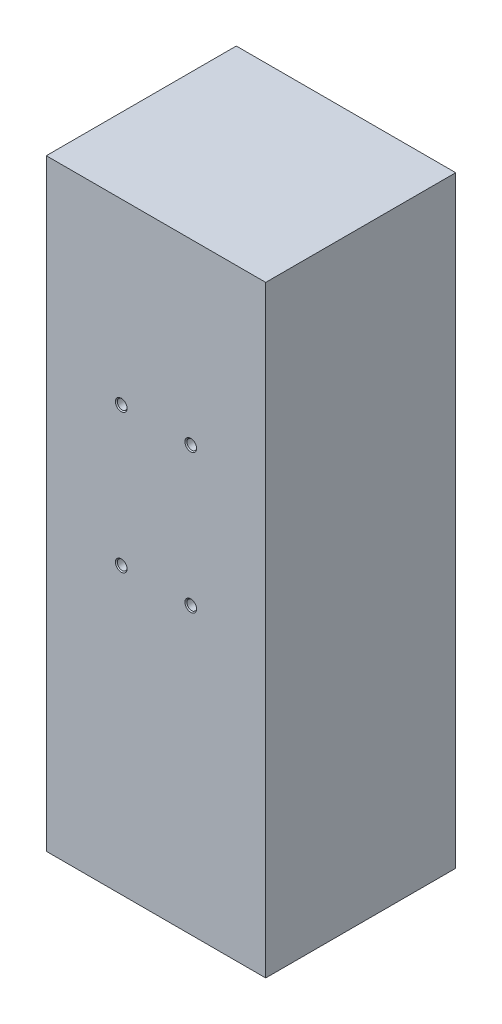
SolidWorks part; units mm, degrees
ref_plane "Front Plane" through (0, 0, 0) normal (0, 0, 1) x (1, 0, 0)
ref_plane "Top Plane" through (0, 0, 0) normal (0, 1, 0) x (1, 0, 0)
ref_plane "Right Plane" through (0, 0, 0) normal (1, 0, 0) x (0, 0, -1)
sketch "Sketch1" plane through (0, 0, 0) normal (0, 1, 0) x (1, 0, 0)
  line L1 (-47.35, -41) -> (47.35, -41)
  line L2 (-47.35, -41) -> (-47.35, 41)
  line L3 (-47.35, 41) -> (47.35, 41)
  line L4 (47.35, -41) -> (47.35, 41)
  line L5 (-47.35, -41) -> (47.35, 41) construction
  line L6 (-47.35, 41) -> (47.35, -41) construction
  point P0 (0, 0)
  dimension "D1" = 94.7
  dimension "D2" = 82
extrude "Boss-Extrude1" add sketch "Sketch1" along normal mid plane 260
sketch "Sketch2" plane through (0, 0, 41) normal (0, 0, 1) x (1, 0, 0)
  line L0 (-47.35, -130) -> (47.35, -130) construction
  line L1 (-15, -7) -> (15, -7) construction
  line L2 (-15, -7) -> (-15, 53) construction
  line L3 (-15, 53) -> (15, 53) construction
  line L4 (15, -7) -> (15, 53) construction
  line L5 (-15, -7) -> (15, 53) construction
  line L6 (-15, 53) -> (15, -7) construction
  line L7 (0, -7) -> (0, -130) construction
  circle A0 centre (15, 53) radius 3 construction
  circle A1 centre (-15, 53) radius 3 construction
  circle A2 centre (-15, -7) radius 3 construction
  circle A3 centre (15, -7) radius 3 construction
  point P0 (0, 23)
  dimension "D4" = 6
  dimension "D1" = 30
  dimension "D2" = 60
  dimension "D3" = 123
hole_wizard "M5x0.8 Tapped Hole1" positions "Sketch3" profile "Sketch4" tap size "M5x0.8" standard "ANSI Metric"
sketch "Sketch3" plane through (0, 0, 41) normal (0, 0, 1) x (1, 0, 0)
  point P0 (15, 53)
  point P3 (-15, 53)
  point P6 (-15, -7)
  point P9 (15, -7)
sketch "Sketch4" plane through (15, 53, 41) normal (1, 0, 0) x (0, -1, 0)
  line L0 (0, 0) -> (0, 13.6618)
  line L1 (0, 13.6618) -> (2.1, 12.4)
  line L2 (2.1, 12.4) -> (2.1, 0.425)
  line L3 (2.1, 0.425) -> (2.525, 0)
  line L5 (2.525, 0) -> (0, 0)
  line L6 (-2.1, 0.425) -> (-2.525, 0) construction
  line L10 (0, 13.6618) -> (-2.1, 12.4) construction
  line L11 (0, -6.35) -> (0, 107.95) construction
  dimension "Tap Drill Dia." = 4.2
  dimension "Tap Drill Depth" = 12.4
  dimension "Near C'Sink Dia." = 5.05
  dimension "Near C'Sink Angle" = 90
  dimension "Drill Angle" = 118
